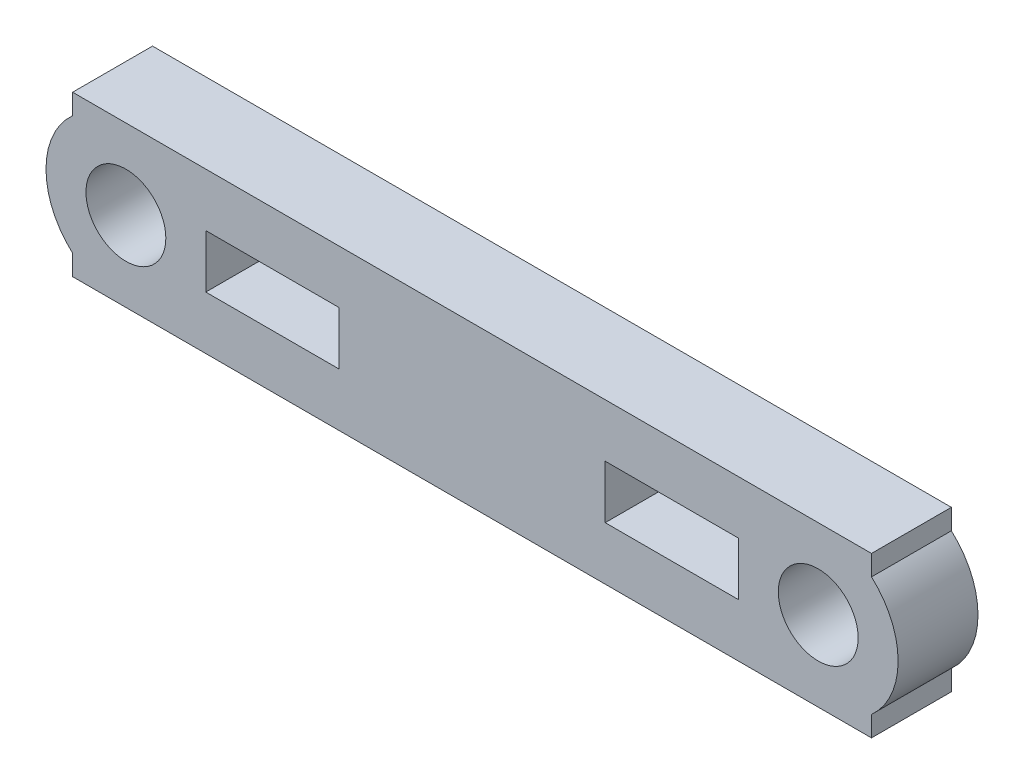
SolidWorks part; units mm, degrees
ref_plane "Front Plane" through (0, 0, 0) normal (0, 0, 1) x (1, 0, 0)
ref_plane "Top Plane" through (0, 0, 0) normal (0, 1, 0) x (1, 0, 0)
ref_plane "Right Plane" through (0, 0, 0) normal (1, 0, 0) x (0, 0, -1)
sketch "Sketch1" plane through (0, 0, 0) normal (0, 0, 1) x (1, 0, 0)
  line L0 (-83.5597, 29.0911) -> (-53.5597, 29.0911)
  line L1 (-53.5597, 29.0911) -> (-53.5597, 23.0911)
  line L2 (-83.5597, 29.0911) -> (-83.5597, 23.0911)
  line L3 (-83.5597, 23.0911) -> (-53.5597, 23.0911)
  line L5 (-78.5597, 26.0911) -> (-78.5597, 27.0911)
  line L6 (-78.5597, 27.0911) -> (-73.5597, 27.0911)
  line L7 (-73.5597, 27.0911) -> (-73.5597, 25.0911)
  line L8 (-73.5597, 25.0911) -> (-78.5597, 25.0911)
  line L9 (-78.5597, 25.0911) -> (-78.5597, 26.0911)
  line L11 (-58.5597, 26.0911) -> (-58.5597, 25.0911)
  line L12 (-58.5597, 25.0911) -> (-63.5597, 25.0911)
  line L13 (-63.5597, 25.0911) -> (-63.5597, 27.0911)
  line L14 (-63.5597, 27.0911) -> (-58.5597, 27.0911)
  line L15 (-58.5597, 27.0911) -> (-58.5597, 26.0911)
  circle A0 centre (-81.5597, 26.0911) radius 1.5
  circle A1 centre (-55.5597, 26.0911) radius 1.5
extrude "Boss-Extrude1" add sketch "Sketch1" along normal blind 3
sketch "Sketch3" plane through (0, 0, 3) normal (0, 0, 1) x (1, 0, 0)
  line L1 (-83.5597, 26.0911) -> (-83.5597, 28.3272)
  line L2 (-83.5597, 29.0911) -> (-83.5597, 23.0911) construction
  line L3 (-83.5597, 26.0911) -> (-83.5597, 23.8551)
  line L4 (-53.5597, 26.0911) -> (-53.5597, 28.3272)
  line L5 (-53.5597, 23.0911) -> (-53.5597, 29.0911) construction
  line L6 (-53.5597, 26.0911) -> (-53.5597, 23.8551)
  arc A0 (-53.5597, 23.8551) -> (-53.5597, 28.3272) centre (-55.5597, 26.0911) ccw
  arc A1 (-83.5597, 28.3272) -> (-83.5597, 23.8551) centre (-81.5597, 26.0911) ccw
extrude "Boss-Extrude3" add sketch "Sketch3" against normal blind 3
